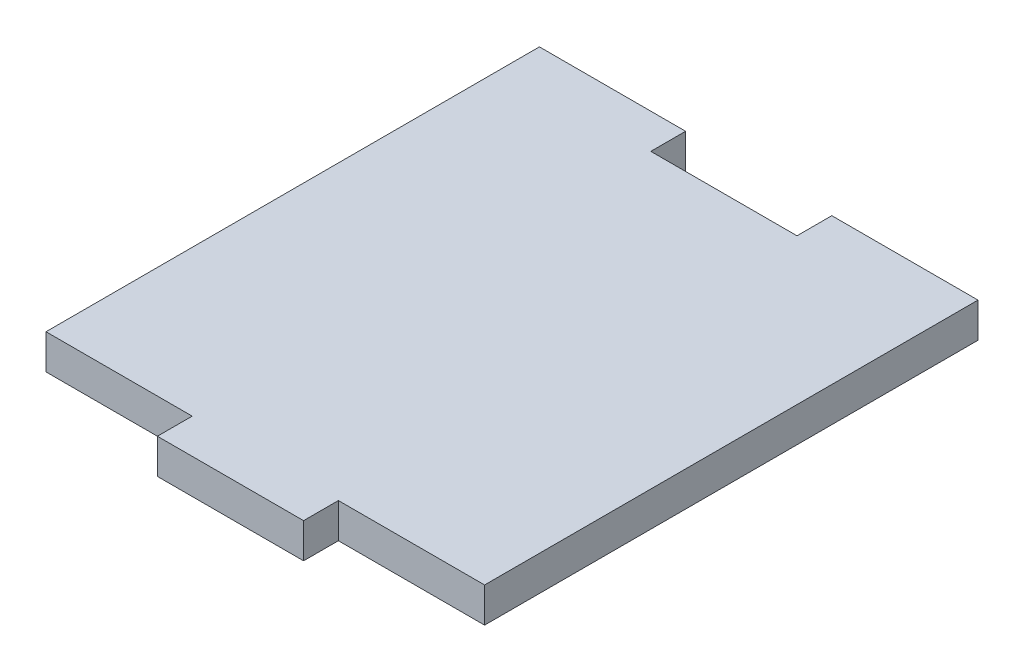
SolidWorks part; units mm, degrees
ref_plane "Front Plane" through (0, 0, 0) normal (0, 0, 1) x (1, 0, 0)
ref_plane "Top Plane" through (0, 0, 0) normal (0, 1, 0) x (1, 0, 0)
ref_plane "Right Plane" through (0, 0, 0) normal (1, 0, 0) x (0, 0, -1)
sketch "Sketch1" plane through (0, 0, 0) normal (0, 1, 0) x (1, 0, 0)
  line L0 (13.3333, 0) -> (13.3333, -3.175)
  line L1 (0, 0) -> (13.3333, 0)
  line L2 (0, 0) -> (0, 45)
  line L3 (0, 45) -> (13.3333, 45)
  line L4 (40, 0) -> (40, 45)
  line L5 (13.3333, -3.175) -> (26.6667, -3.175)
  line L6 (26.6667, -3.175) -> (26.6667, 0)
  line L7 (26.6667, 0) -> (40, 0)
  line L8 (13.3333, 45) -> (13.3333, 41.825)
  line L9 (13.3333, 41.825) -> (26.6667, 41.825)
  line L10 (26.6667, 41.825) -> (26.6667, 45)
  line L11 (26.6667, 45) -> (40, 45)
  dimension "D1" = 45
  dimension "D2" = 40
  dimension "D3" = 3.175
  dimension "D4" = 3.175
extrude "Boss-Extrude1" add sketch "Sketch1" along normal blind 3.175
